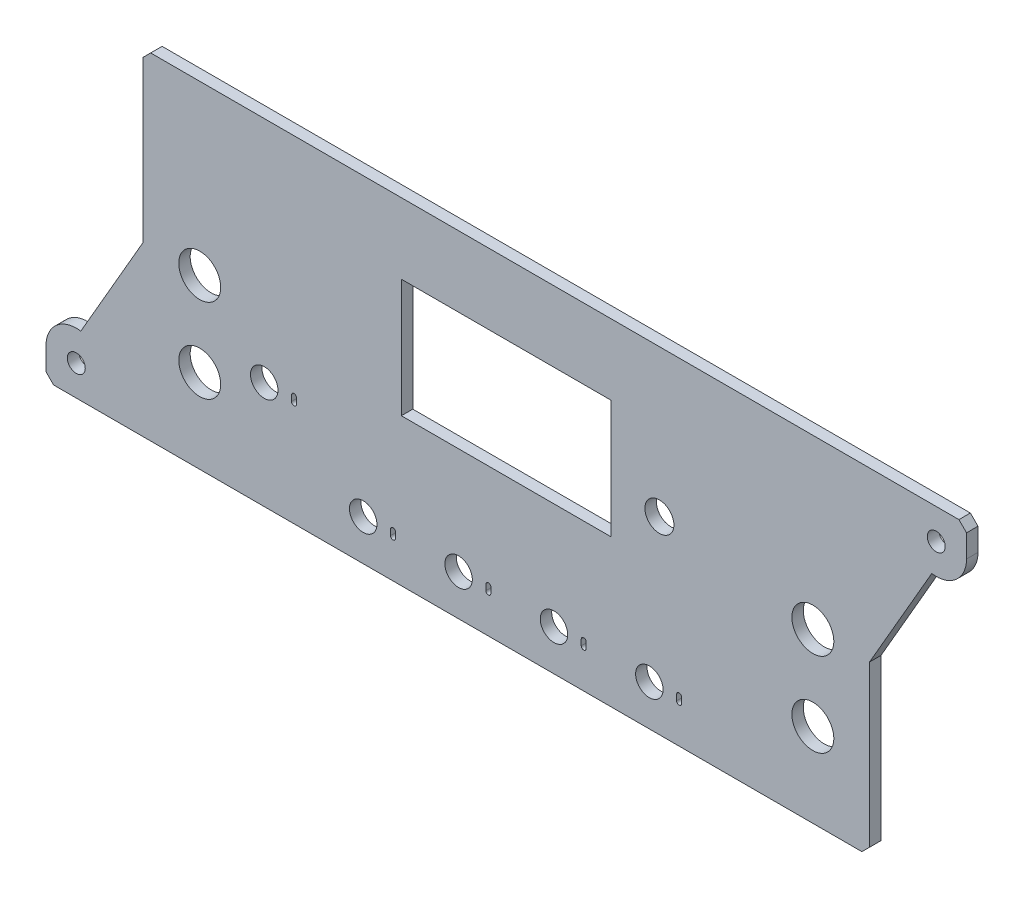
SolidWorks part; units mm, degrees
ref_plane "Front Plane" through (0, 0, 0) normal (0, 0, 1) x (1, 0, 0)
ref_plane "Top Plane" through (0, 0, 0) normal (0, 1, 0) x (1, 0, 0)
ref_plane "Right Plane" through (0, 0, 0) normal (1, 0, 0) x (0, 0, -1)
sketch "Sketch1" plane through (0, 0, 0) normal (0, 0, 1) x (1, 0, 0)
  line L0 (-120.65, 0) -> (120.65, 0) construction
  line L1 (-120.65, -44.05) -> (120.65, -44.05)
  line L2 (-120.65, -44.05) -> (-120.65, 44.05)
  line L3 (-120.65, 44.05) -> (120.65, 44.05)
  line L4 (120.65, -44.05) -> (120.65, 44.05)
  line L5 (-120.65, -44.05) -> (120.65, 44.05) construction
  line L6 (-120.65, 44.05) -> (120.65, -44.05) construction
  line L7 (0, 44.05) -> (0, -44.05) construction
  line L8 (-120.65, -44.05) -> (-95.2177, 0)
  line L9 (-27.5, -5.45) -> (27.5, -5.45)
  line L10 (-27.5, -5.45) -> (-27.5, 25.55)
  line L11 (-27.5, 25.55) -> (27.5, 25.55)
  line L12 (27.5, -5.45) -> (27.5, 25.55)
  line L13 (-27.5, -5.45) -> (27.5, 25.55) construction
  line L14 (-27.5, 25.55) -> (27.5, -5.45) construction
  line L15 (-95.2177, 0) -> (-95.2177, 44.05)
  line L16 (120.65, 44.05) -> (95.2177, 0)
  line L17 (95.2177, 0) -> (95.2177, -44.05)
  line L18 (-112.71, 44.05) -> (-112.71, -44.05) construction
  line L19 (-120.65, 36.11) -> (120.65, 36.11) construction
  line L20 (-120.65, -36.11) -> (120.65, -36.11) construction
  line L21 (112.71, 44.05) -> (112.71, -44.05) construction
  line L22 (65.2876, 38.3607) -> (-42.7124, 38.3607) construction
  line L27 (65.2876, 38.3607) -> (-42.7124, 38.3607)
  line L28 (-29.7, -32.5946) -> (-29.7, -34.0946) construction
  line L29 (-42.5, 38.3607) -> (65.5, 38.3607)
  line L30 (-42.5, 38.3607) -> (-42.5, -22.6393)
  line L31 (-42.5, -22.6393) -> (65.5, -22.6393)
  line L32 (65.5, 38.3607) -> (65.5, -22.6393)
  line L33 (-29.05, -32.5946) -> (-29.05, -34.0946)
  line L34 (-30.35, -32.5946) -> (-30.35, -34.0946)
  line L35 (0, -22.6393) -> (0, -44.05) construction
  line L42 (-5.35, -32.5946) -> (-5.35, -34.0946)
  line L45 (-12.5, -33.3446) -> (12.5, -33.3446) construction
  line L46 (-4.05, -32.5946) -> (-4.05, -34.0946)
  line L47 (-4.7, -32.5946) -> (-4.7, -34.0946) construction
  line L48 (19.65, -32.5946) -> (19.65, -34.0946)
  line L49 (20.95, -32.5946) -> (20.95, -34.0946)
  line L50 (20.3, -32.5946) -> (20.3, -34.0946) construction
  line L51 (44.65, -32.5946) -> (44.65, -34.0946)
  line L52 (45.95, -32.5946) -> (45.95, -34.0946)
  line L53 (45.3, -32.5946) -> (45.3, -34.0946) construction
  line L54 (65.5, 0) -> (95.2177, 0)
  line L55 (-80.3577, 0) -> (-80.3577, -44.05) construction
  line L56 (80.3589, 0) -> (80.3589, -44.05) construction
  line L57 (-80.3577, -22.025) -> (-63.4433, -15.8686)
  line L58 (-55.6433, -15.1186) -> (-55.6433, -16.6186) construction
  line L61 (-54.9933, -15.1186) -> (-54.9933, -16.6186)
  line L62 (-56.2933, -15.1186) -> (-56.2933, -16.6186)
  line L63 (95.2177, -42.05) -> (93.2177, -44.05)
  line L64 (-93.2177, 44.05) -> (-95.2177, 42.05)
  line L65 (-120.65, -42.05) -> (-118.65, -44.05)
  line L66 (118.65, 44.05) -> (120.65, 42.05)
  circle A0 centre (-112.71, 36.11) radius 2.35
  circle A1 centre (112.71, 36.11) radius 2.35
  circle A2 centre (112.71, -36.11) radius 2.35
  circle A3 centre (-112.71, -36.11) radius 2.35
  arc A5 (40.1376, 9.2607) -> (40.1376, 1.6607) centre (40.1376, 5.4607) ccw construction
  arc A6 (40.1376, 1.6607) -> (40.1376, 9.2607) centre (40.1376, 5.4607) ccw construction
  arc A7 (40.1376, 9.2607) -> (40.1376, 1.6607) centre (40.1376, 5.4607) ccw
  arc A8 (40.1376, 1.6607) -> (40.1376, 9.2607) centre (40.1376, 5.4607) ccw
  arc A9 (-29.05, -32.5946) -> (-30.35, -32.5946) centre (-29.7, -32.5946) ccw
  arc A10 (-30.35, -34.0946) -> (-29.05, -34.0946) centre (-29.7, -34.0946) ccw
  circle A11 centre (-37.5, -33.3446) radius 3.6
  circle A21 centre (-12.5, -33.3446) radius 3.6
  circle A22 centre (12.5, -33.3446) radius 3.6
  circle A23 centre (37.5, -33.3446) radius 3.6
  arc A26 (-4.05, -32.5946) -> (-5.35, -32.5946) centre (-4.7, -32.5946) ccw
  arc A27 (-5.35, -34.0946) -> (-4.05, -34.0946) centre (-4.7, -34.0946) ccw
  arc A28 (20.95, -32.5946) -> (19.65, -32.5946) centre (20.3, -32.5946) ccw
  arc A29 (19.65, -34.0946) -> (20.95, -34.0946) centre (20.3, -34.0946) ccw
  arc A30 (45.95, -32.5946) -> (44.65, -32.5946) centre (45.3, -32.5946) ccw
  arc A31 (44.65, -34.0946) -> (45.95, -34.0946) centre (45.3, -34.0946) ccw
  circle A32 centre (80.3589, 0) radius 5.5
  circle A33 centre (-80.3577, 0) radius 5.5
  circle A34 centre (-80.3577, -22.025) radius 5.5
  circle A35 centre (80.3589, -22.025) radius 5.5
  circle A36 centre (-80.3577, -22.025) radius 7.5
  circle A37 centre (-63.4433, -15.8686) radius 8.5
  circle A38 centre (-63.4433, -15.8686) radius 3.6
  arc A41 (-54.9933, -15.1186) -> (-56.2933, -15.1186) centre (-55.6433, -15.1186) ccw
  arc A42 (-56.2933, -16.6186) -> (-54.9933, -16.6186) centre (-55.6433, -16.6186) ccw
  arc A43 (120.65, 36.11) -> (111.5324, 28.2578) centre (112.71, 36.11) cw
  arc A44 (-120.65, -36.11) -> (-111.5324, -28.2578) centre (-112.71, -36.11) cw
  point P0 (0, 0)
  point P10 (0, 10.05)
  point P27 (-112.71, 36.11)
  point P28 (-112.71, -36.11)
  point P29 (112.71, 36.11)
  point P30 (112.71, -36.11)
  point P39 (-29.7, -33.3446)
  point P50 (0, -33.3446)
  point P58 (-37.5, -33.3446)
  point P59 (-29.7, -31.9446)
  point P60 (-29.7, -34.7446)
  point P61 (0, -22.6393)
  point P66 (0, -33.3446)
  point P72 (-4.7, -33.3446)
  point P80 (20.3, -33.3446)
  point P87 (45.3, -33.3446)
  point P94 (65.5, 0)
  point P107 (-71.4306, -18.7758)
  point P108 (-73.31, -19.4598)
  point P112 (-55.6433, -15.8686)
  point P117 (-55.6433, -14.4686)
  point P118 (-55.6433, -17.2686)
  dimension "D9" = 4.7
  dimension "D10" = 1.3
  dimension "D13" = 7.2
  dimension "D14" = 11
  dimension "D18" = 11
  dimension "D20" = 11
  dimension "D21" = 11
  dimension "D22" = 15
  dimension "D23" = 17
  dimension "D25" = 2
  dimension "D26" = 7.2
  dimension "D1" = 241.3
  dimension "D2" = 88.1
  dimension "D3" = 55
  dimension "D4" = 31
  dimension "D5" = 34
  dimension "D6" = 60
  dimension "D7" = 7.94
  dimension "D8" = 7.94
  dimension "D11" = 2.8
  dimension "D12" = 7.8
  dimension "D15" = 61
  dimension "D16" = 108
  dimension "D17" = 15
  dimension "D19" = 14.86
  dimension "D24" = 20
  dimension "D28" = 2.8
  dimension "D29" = 1.3
  dimension "D30" = 7.8
  dimension "D31" = 2
  dimension "D32" = 2
  dimension "D33" = 2
  dimension "D34" = 2
  dimension "D35" = 2
  dimension "D36" = 2
  dimension "D37" = 2
  dimension "D38" = 2
  dimension "D27" = 4
extrude "Boss-Extrude1" add sketch "Sketch1" along normal blind 3
